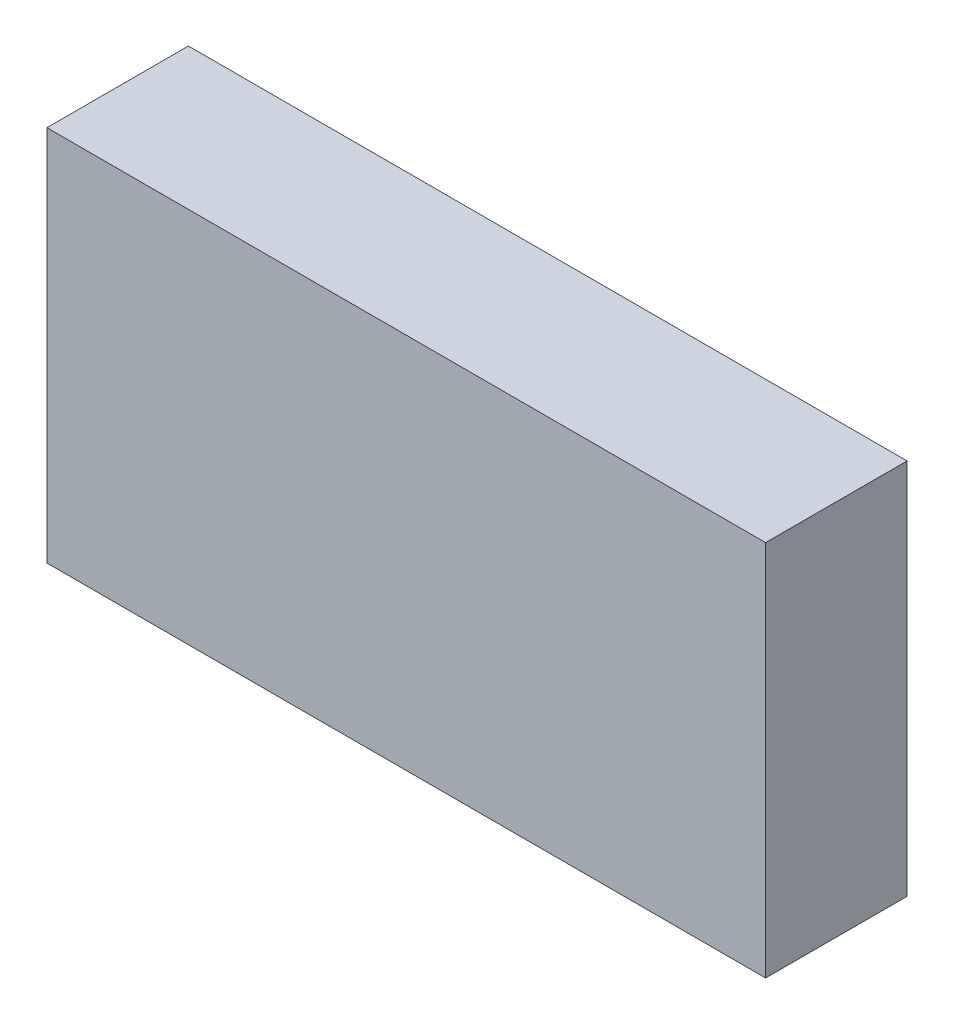
SolidWorks part; units mm, degrees
material "Brass"
ref_plane "Front Plane" through (0, 0, 0) normal (0, 0, 1) x (1, 0, 0)
ref_plane "Top Plane" through (0, 0, 0) normal (0, 1, 0) x (1, 0, 0)
ref_plane "Right Plane" through (0, 0, 0) normal (1, 0, 0) x (0, 0, -1)
sketch "Sketch1" plane through (0, 0, 0) normal (0, 0, 1) x (1, 0, 0)
  line L1 (0, 0) -> (101.6, 0)
  line L2 (0, 0) -> (0, 53.3)
  line L3 (0, 53.3) -> (101.6, 53.3)
  line L4 (101.6, 0) -> (101.6, 53.3)
  dimension "D1" = 53.3
  dimension "D2" = 101.6
extrude "Boss-Extrude1" add sketch "Sketch1" along normal blind 20
